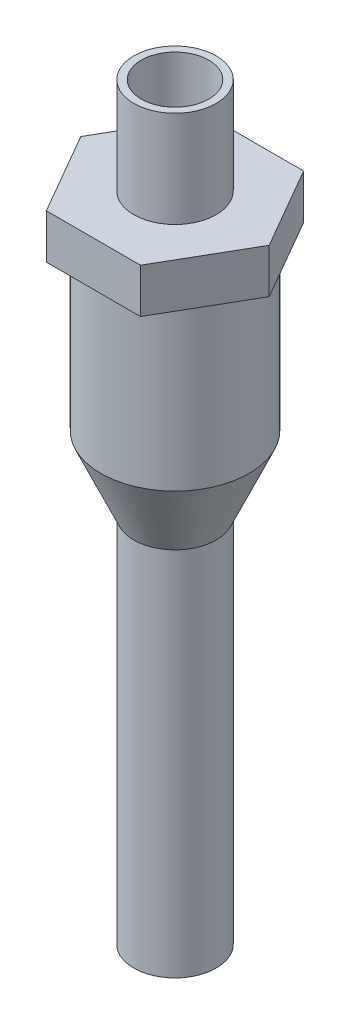
SolidWorks part; units mm, degrees
material "6061-T6"
ref_plane "Front" through (0, 0, 0) normal (0, 0, 1) x (1, 0, 0)
ref_plane "Top" through (0, 0, 0) normal (0, 1, 0) x (1, 0, 0)
ref_plane "Right" through (0, 0, 0) normal (1, 0, 0) x (0, 0, -1)
sketch "Sketch1" plane through (0, 0, 0) normal (0, 0, 1) x (1, 0, 0)
  line L0 (0, 13) -> (0, -88) construction
  line L1 (0, 13) -> (5.5563, 13)
  line L2 (5.5563, 13) -> (5.5562, 0)
  line L3 (5.5562, 0) -> (10, 0)
  line L4 (10, 0) -> (10, -28)
  line L5 (10, -28) -> (5.5563, -38)
  line L6 (5.5563, -38) -> (5.5563, -88)
  line L7 (5.5563, -88) -> (0, -88)
  line L8 (0, -88) -> (0, 13)
  dimension "D1" = 11.1125
  dimension "D2" = 13
  dimension "D3" = 28
  dimension "D4" = 10
  dimension "D5" = 50
  dimension "D6" = 20
revolve "Revolve1" add sketch "Sketch1" angle 360 about L0
cosmetic thread "Cosmetic Thread1" parameters "D1"=10, "D2"=9.6012
sketch "Sketch2" plane through (0, 0, 0) normal (0, 1, 0) x (1, 0, 0)
  line L0 (0, 0) -> (8.6603, 5) construction
  line L1 (12.7017, 0) -> (6.3509, 11)
  line L2 (6.3509, 11) -> (-6.3509, 11)
  line L3 (-6.3509, 11) -> (-12.7017, 0)
  line L4 (-12.7017, 0) -> (-6.3509, -11)
  line L5 (-6.3509, -11) -> (6.3509, -11)
  line L6 (6.3509, -11) -> (12.7017, 0)
  line L7 (8.6603, 5) -> (9.5263, 5.5) construction
  circle A0 centre (0, 0) radius 11 construction
  circle A2 centre (0, 0) radius 10 construction
  dimension "D1" = 1
extrude "Boss-Extrude1" add sketch "Sketch2" against normal blind 6
sketch "Sketch3" plane through (0, 13, 0) normal (0, 1, 0) x (1, 0, 0)
  circle A2 centre (0, 0) radius 4.5562
  circle A3 centre (0, 0) radius 4.5562
  dimension "D1" = 1
extrude "Cut-Extrude1" cut sketch "Sketch3" against normal offset from surface (99 mm away) 2 up to face at (-5.5562, -88, 0)
